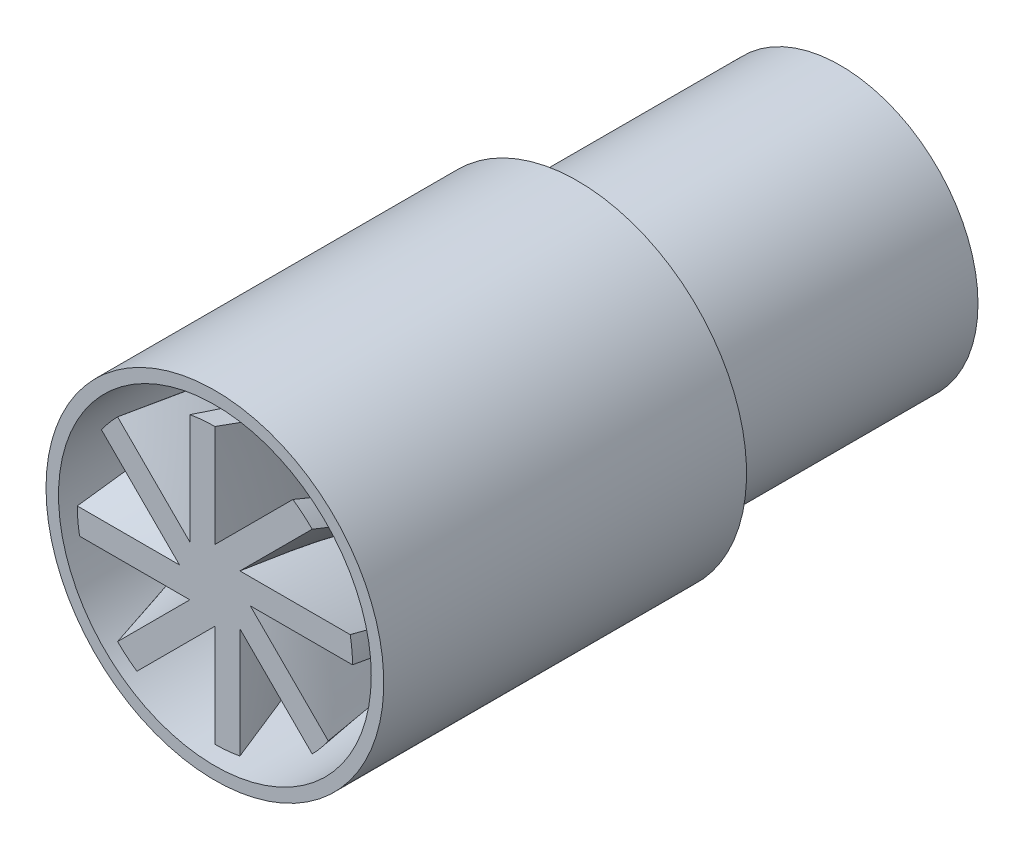
SolidWorks part; units mm, degrees
ref_plane "Front Plane" through (0, 0, 0) normal (0, 0, 1) x (1, 0, 0)
ref_plane "Top Plane" through (0, 0, 0) normal (0, 1, 0) x (1, 0, 0)
ref_plane "Right Plane" through (0, 0, 0) normal (1, 0, 0) x (0, 0, -1)
sketch "Sketch1" plane through (0, 0, 0) normal (0, 0, 1) x (1, 0, 0)
  circle A0 centre (0, 0) radius 13.5
  dimension "D1" = 27
extrude "Boss-Extrude1" add sketch "Sketch1" along normal blind 29
sketch "Sketch2" plane through (0, 0, 0) normal (0, 0, -1) x (-1, 0, 0)
  circle A0 centre (0, 0) radius 11
  dimension "D1" = 22
extrude "Boss-Extrude2" add sketch "Sketch2" along normal blind 21
sketch "Sketch3" plane through (0, 0, 29) normal (0, 0, 1) x (1, 0, 0)
  circle A0 centre (0, 0) radius 12.5
  circle A1 centre (0, 0) radius 13.5
  circle A2 centre (0, 0) radius 13.5
  circle A3 centre (0, 0) radius 2.5
  dimension "D1" = 0
  dimension "D2" = 1
  dimension "D3" = 11
extrude "Cut-Extrude1" cut sketch "Sketch3" against normal blind 29 contours A0 A3
sketch "Sketch5" plane through (0, 0, 0) normal (0, 0, 1) x (1, 0, 0)
  line L0 (0, 0) -> (7.7782, 7.7782)
  line L2 (11, 0) -> (0, 0)
  line L3 (0, 0) -> (7.7782, 7.7782)
  line L4 (0, 0) -> (-1.4142, 1.4142)
  line L5 (7.7782, 7.7782) -> (6.364, 9.1924)
  line L6 (-1.4142, 1.4142) -> (6.364, 9.1924)
  line L8 (0, 0) -> (11, 0)
  line L9 (0, 0) -> (0, -2)
  line L10 (0, -2) -> (10.8167, -2)
  arc A0 (10.8167, -2) -> (11, 0) centre (0, 0) ccw
  circle A1 centre (0, 0) radius 11
  arc A2 (7.7782, 7.7782) -> (6.2343, 9.0627) centre (0, 0) ccw
  dimension "D2" = 45
  dimension "D3" = 2
  dimension "D1" = 0
sketch "Sketch6" plane through (0, 0, 29) normal (0, 0, 1) x (1, 0, 0)
  line L0 (0, 0) -> (7.7782, 7.7782) construction
  line L1 (0, 0) -> (-1.4142, 1.4142) construction
  line L2 (-1.4142, 1.4142) -> (6.364, 9.1924) construction
  line L3 (0, 0) -> (7.7782, 7.7782)
  line L4 (0, 0) -> (-1.4142, 1.4142)
  line L5 (-1.4142, 1.4142) -> (6.2343, 9.0627)
  arc A0 (7.7782, 7.7782) -> (6.2343, 9.0627) centre (0, 0) ccw construction
  arc A1 (7.7782, 7.7782) -> (6.2343, 9.0627) centre (0, 0) ccw
sketch "Sketch7" plane through (0, 0, 0) normal (1, 0, 0) x (0, 0, -1)
  line L0 (0, 0) -> (-29, 0)
  line L1 (-29, 0) -> (-29, 1.4142) construction
loft "Loft1" add profiles "Sketch6" section "Sketch5" section "Sketch6"
pattern_circular "CirPattern1" count 8 every 45 of "Loft1"
